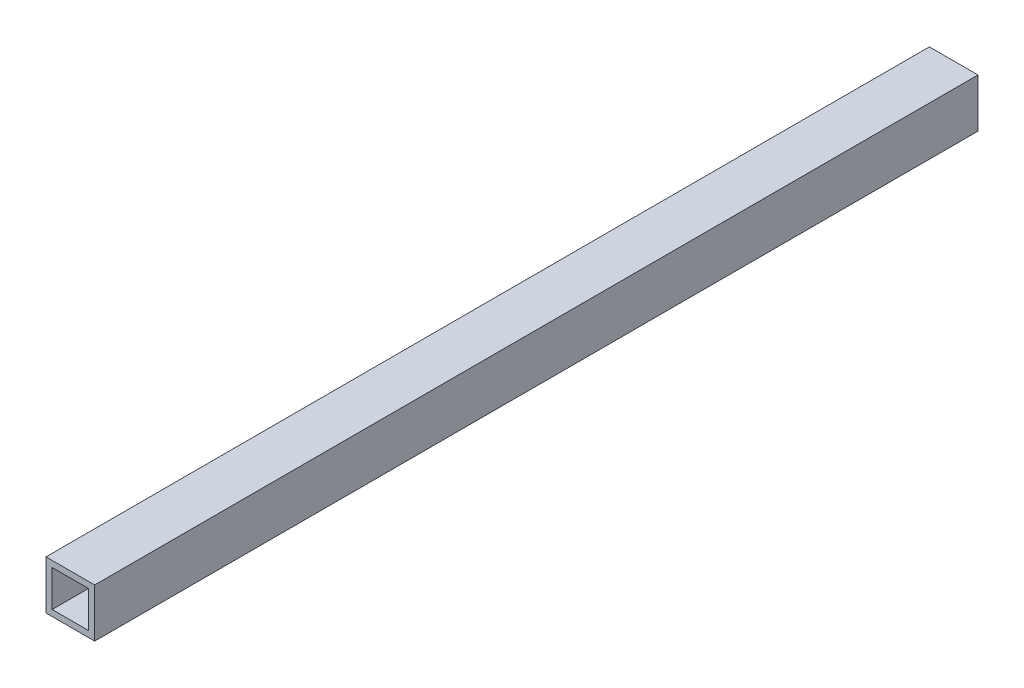
SolidWorks part; units mm, degrees
ref_plane "Front Plane" through (0, 0, 0) normal (0, 0, 1) x (1, 0, 0)
ref_plane "Top Plane" through (0, 0, 0) normal (0, 1, 0) x (1, 0, 0)
ref_plane "Right Plane" through (0, 0, 0) normal (1, 0, 0) x (0, 0, -1)
sketch "Sketch1" plane through (0, 0, 0) normal (0, 0, 1) x (1, 0, 0)
  line L1 (-6.06, 6.06) -> (6.06, 6.06)
  line L2 (-6.06, 6.06) -> (-6.06, -6.06)
  line L3 (-6.06, -6.06) -> (6.06, -6.06)
  line L4 (6.06, 6.06) -> (6.06, -6.06)
  line L5 (-6.06, 6.06) -> (6.06, -6.06) construction
  line L6 (-6.06, -6.06) -> (6.06, 6.06) construction
  line L7 (-4.53, 4.53) -> (4.53, 4.53)
  line L8 (-4.53, 4.53) -> (-4.53, -4.53)
  line L9 (-4.53, -4.53) -> (4.53, -4.53)
  line L10 (4.53, 4.53) -> (4.53, -4.53)
  line L11 (-4.53, 4.53) -> (4.53, -4.53) construction
  line L12 (-4.53, -4.53) -> (4.53, 4.53) construction
  point P0 (0, 0)
  point P6 (0, 0)
  dimension "D1" = 1.53
  dimension "D2" = 12.12
extrude "Boss-Extrude1" add sketch "Sketch1" along normal mid plane 220
